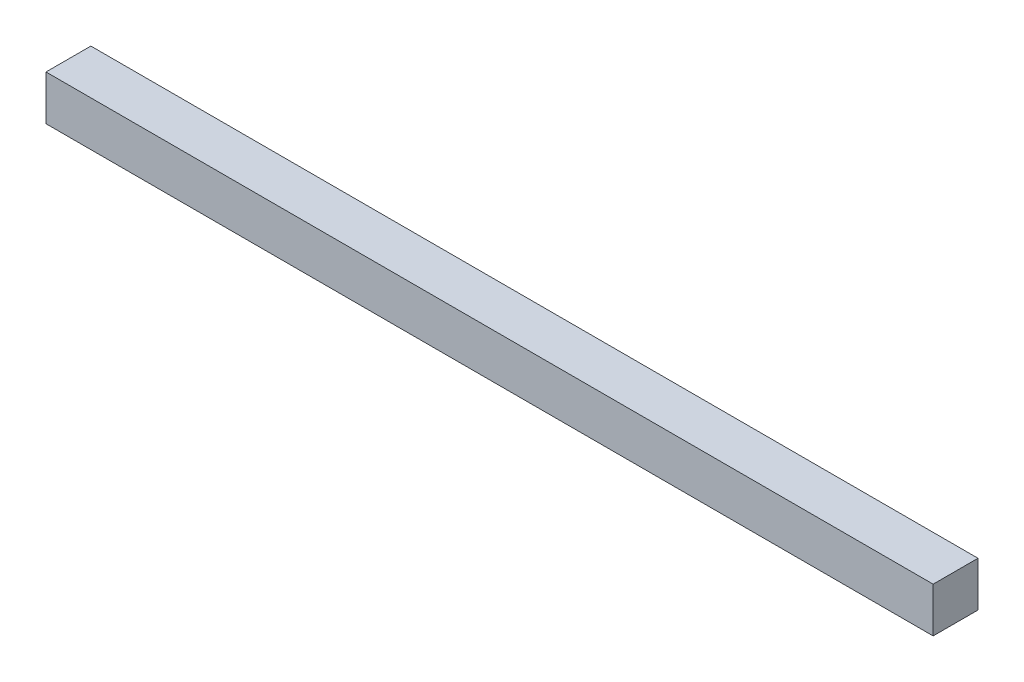
SolidWorks part; units mm, degrees
ref_plane "Front Plane" through (0, 0, 0) normal (0, 0, 1) x (1, 0, 0)
ref_plane "Top Plane" through (0, 0, 0) normal (0, 1, 0) x (1, 0, 0)
ref_plane "Right Plane" through (0, 0, 0) normal (1, 0, 0) x (0, 0, -1)
sketch "Sketch1" plane through (0, 0, 0) normal (0, 0, 1) x (1, 0, 0)
  line L0 (-89, 0) -> (89, 0) construction
  dimension "D1" = 178
sketch "Sketch2" plane through (0, 0, 0) normal (1, 0, 0) x (0, 0, -1)
  line L1 (-4.5, -4.5) -> (4.5, -4.5)
  line L2 (-4.5, -4.5) -> (-4.5, 4.5)
  line L3 (-4.5, 4.5) -> (4.5, 4.5)
  line L4 (4.5, -4.5) -> (4.5, 4.5)
  line L5 (-4.5, -4.5) -> (4.5, 4.5) construction
  line L6 (-4.5, 4.5) -> (4.5, -4.5) construction
  point P0 (0, 0)
  dimension "D1" = 9
extrude "Boss-Extrude1" add sketch "Sketch2" along normal up to vertex (89 mm away) and the other way up to vertex (89 mm away) up to point (89, 0, 0) other way up to point (-89, 0, 0)
